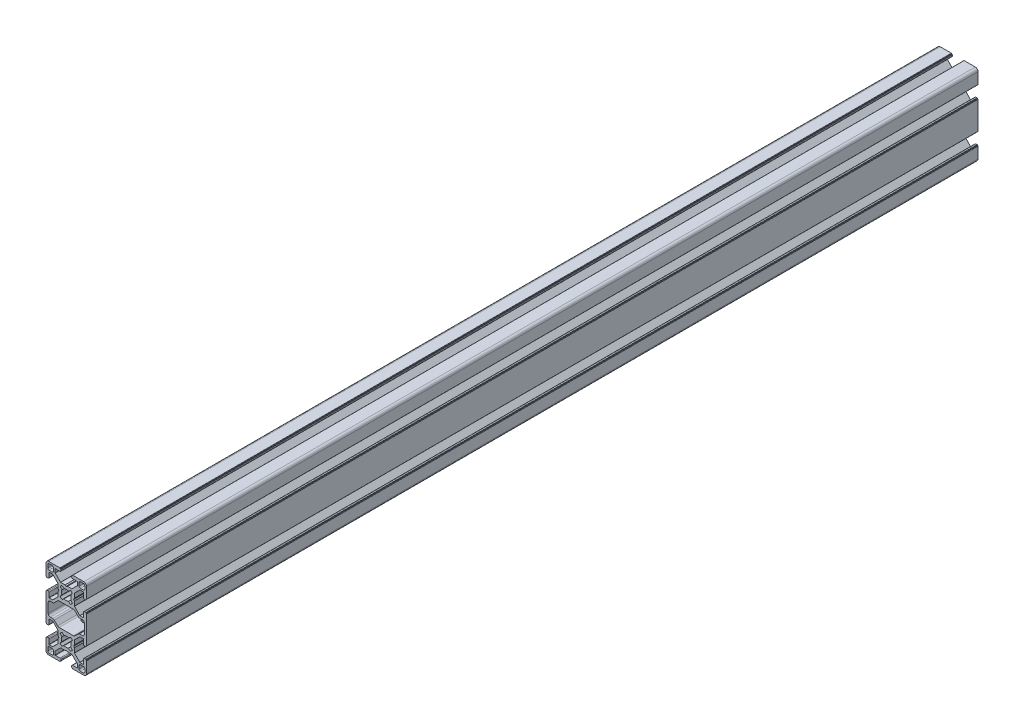
SolidWorks part; units mm, degrees
material "1060 Alloy"
ref_plane "Front" through (0, 0, 0) normal (0, 0, 1) x (1, 0, 0)
ref_plane "Top" through (0, 0, 0) normal (0, 1, 0) x (1, 0, 0)
ref_plane "Right" through (0, 0, 0) normal (1, 0, 0) x (0, 0, -1)
ref_plane "Plane1" through (0, 0, 25) normal (0, 0, 1) x (1, 0, 0)
sketch "Sketch1" plane through (0, 0, 25) normal (0, 0, 1) x (1, 0, 0)
  line L0 (-9.5, 12.7) -> (-9.5, 10.5)
  line L1 (-10.5, 9.5) -> (-12.7, 9.5)
  line L2 (-13.7, 10.5) -> (-13.7, 12.7)
  line L3 (-12.7, 13.7) -> (-10.5, 13.7)
  line L4 (12.7, 9.5) -> (10.5, 9.5)
  line L5 (9.5, 10.5) -> (9.5, 12.7)
  line L6 (10.5, 13.7) -> (12.7, 13.7)
  line L7 (13.7, 12.7) -> (13.7, 10.5)
  line L8 (-12.7, -39.5) -> (-10.5, -39.5)
  line L9 (-9.5, -40.5) -> (-9.5, -42.7)
  line L10 (-10.5, -43.7) -> (-12.7, -43.7)
  line L11 (-13.7, -42.7) -> (-13.7, -40.5)
  line L12 (9.5, -42.7) -> (9.5, -40.5)
  line L13 (10.5, -39.5) -> (12.7, -39.5)
  line L14 (13.7, -40.5) -> (13.7, -42.7)
  line L15 (12.7, -43.7) -> (10.5, -43.7)
  line L16 (-3.2806, 1.6001) -> (-4.5184, 3.1359)
  line L17 (-3.1547, 4.5053) -> (-1.6001, 3.2806)
  line L18 (1.6001, 3.2806) -> (3.1547, 4.5053)
  line L19 (4.5184, 3.1359) -> (3.2806, 1.6001)
  line L20 (3.2806, -1.6001) -> (4.5184, -3.1359)
  line L21 (3.1547, -4.5053) -> (1.6001, -3.2806)
  line L22 (-1.6001, -3.2806) -> (-3.1547, -4.5053)
  line L23 (-4.5184, -3.1359) -> (-3.2806, -1.6001)
  line L24 (-4.5184, -33.1359) -> (-3.2806, -31.6001)
  line L25 (-3.2806, -28.3999) -> (-4.5184, -26.8641)
  line L26 (-3.1547, -25.4947) -> (-1.6001, -26.7194)
  line L27 (1.6001, -26.7194) -> (3.1547, -25.4947)
  line L28 (4.5184, -26.8641) -> (3.2806, -28.3999)
  line L29 (3.2806, -31.6001) -> (4.5184, -33.1359)
  line L30 (3.1547, -34.5053) -> (1.6001, -33.2806)
  line L31 (-1.6001, -33.2806) -> (-3.1547, -34.5053)
  line L32 (8.9272, -20.5393) -> (6.4104, -23.0562)
  line L33 (5.3497, -23.4955) -> (-5.3497, -23.4955)
  line L34 (-6.4104, -23.0562) -> (-8.9272, -20.5393)
  line L35 (-9.9879, -20.1) -> (-11.85, -20.1)
  line L36 (-13.35, -18.6) -> (-13.35, -11.4)
  line L37 (-11.85, -9.9) -> (-9.9879, -9.9)
  line L38 (-8.9272, -9.4607) -> (-6.4104, -6.9438)
  line L39 (-5.3497, -6.5045) -> (5.3497, -6.5045)
  line L40 (6.4104, -6.9438) -> (8.9272, -9.4607)
  line L41 (9.9879, -9.9) -> (11.85, -9.9)
  line L42 (13.35, -11.4) -> (13.35, -18.6)
  line L43 (11.85, -20.1) -> (9.9879, -20.1)
  line L44 (13.4, -25.95) -> (14.3, -25.95)
  line L45 (14.5, -25.75) -> (14.5, -25.65)
  line L46 (14.7, -25.45) -> (14.8, -25.45)
  line L47 (15, -25.25) -> (15, -4.75)
  line L48 (14.8, -4.55) -> (14.7, -4.55)
  line L49 (14.5, -4.35) -> (14.5, -4.25)
  line L50 (14.3, -4.05) -> (13.4, -4.05)
  line L51 (12.8, -4.65) -> (12.8, -8.05)
  line L52 (12.6, -8.25) -> (10.1328, -8.25)
  line L53 (9.9914, -8.1914) -> (6.063, -4.263)
  line L54 (6.0045, -4.1216) -> (6.0045, -0.9)
  line L55 (6.0045, -0.9) -> (5.5426, -0.1)
  line L56 (5.5426, 0.1) -> (6.0045, 0.9)
  line L57 (6.0045, 0.9) -> (6.0045, 4.1216)
  line L58 (6.063, 4.263) -> (9.9914, 8.1914)
  line L59 (10.1328, 8.25) -> (12.6, 8.25)
  line L60 (12.8, 8.05) -> (12.8, 4.65)
  line L61 (13.4, 4.05) -> (14.3, 4.05)
  line L62 (14.5, 4.25) -> (14.5, 4.35)
  line L63 (14.7, 4.55) -> (14.8, 4.55)
  line L64 (15, 4.75) -> (15, 13)
  line L65 (13, 15) -> (4.75, 15)
  line L66 (4.55, 14.8) -> (4.55, 14.7)
  line L67 (4.35, 14.5) -> (4.25, 14.5)
  line L68 (4.05, 14.3) -> (4.05, 13.4)
  line L69 (4.65, 12.8) -> (8.05, 12.8)
  line L70 (8.25, 12.6) -> (8.25, 10.1328)
  line L71 (8.1914, 9.9914) -> (4.2586, 6.0586)
  line L72 (4.1172, 6) -> (0.9, 6)
  line L73 (0.9, 6) -> (0.1019, 5.5392)
  line L74 (-0.1019, 5.5392) -> (-0.9, 6)
  line L75 (-0.9, 6) -> (-4.1172, 6)
  line L76 (-4.2586, 6.0586) -> (-8.1914, 9.9914)
  line L77 (-8.25, 10.1328) -> (-8.25, 12.6)
  line L78 (-8.05, 12.8) -> (-4.65, 12.8)
  line L79 (-4.05, 13.4) -> (-4.05, 14.3)
  line L80 (-4.25, 14.5) -> (-4.35, 14.5)
  line L81 (-4.55, 14.7) -> (-4.55, 14.8)
  line L82 (-4.75, 15) -> (-13, 15)
  line L83 (-15, 13) -> (-15, 4.75)
  line L84 (-14.8, 4.55) -> (-14.7, 4.55)
  line L85 (-14.5, 4.35) -> (-14.5, 4.25)
  line L86 (-14.3, 4.05) -> (-13.4, 4.05)
  line L87 (-12.8, 4.65) -> (-12.8, 8.05)
  line L88 (-12.6, 8.25) -> (-10.1328, 8.25)
  line L89 (-9.9914, 8.1914) -> (-6.063, 4.263)
  line L90 (-6.0045, 4.1216) -> (-6.0045, 0.9)
  line L91 (-6.0045, 0.9) -> (-5.5426, 0.1)
  line L92 (-5.5426, -0.1) -> (-6.0045, -0.9)
  line L93 (-6.0045, -0.9) -> (-6.0045, -4.1216)
  line L94 (-6.063, -4.263) -> (-9.9914, -8.1914)
  line L95 (-10.1328, -8.25) -> (-12.6, -8.25)
  line L96 (-12.8, -8.05) -> (-12.8, -4.65)
  line L97 (-13.4, -4.05) -> (-14.3, -4.05)
  line L98 (-14.5, -4.25) -> (-14.5, -4.35)
  line L99 (-14.7, -4.55) -> (-14.8, -4.55)
  line L100 (-15, -4.75) -> (-15, -25.25)
  line L101 (-14.8, -25.45) -> (-14.7, -25.45)
  line L102 (-14.5, -25.65) -> (-14.5, -25.75)
  line L103 (-14.3, -25.95) -> (-13.4, -25.95)
  line L104 (-12.8, -25.35) -> (-12.8, -21.95)
  line L105 (-12.6, -21.75) -> (-10.1328, -21.75)
  line L106 (-9.9914, -21.8086) -> (-6.063, -25.737)
  line L107 (-6.0045, -25.8784) -> (-6.0045, -29.1)
  line L108 (-6.0045, -29.1) -> (-5.5426, -29.9)
  line L109 (-5.5426, -30.1) -> (-6.0045, -30.9)
  line L110 (-6.0045, -30.9) -> (-6.0045, -34.1216)
  line L111 (-6.063, -34.263) -> (-9.9914, -38.1914)
  line L112 (-10.1328, -38.25) -> (-12.6, -38.25)
  line L113 (-12.8, -38.05) -> (-12.8, -34.65)
  line L114 (-13.4, -34.05) -> (-14.3, -34.05)
  line L115 (-14.5, -34.25) -> (-14.5, -34.35)
  line L116 (-14.7, -34.55) -> (-14.8, -34.55)
  line L117 (-15, -34.75) -> (-15, -43)
  line L118 (-13, -45) -> (-4.75, -45)
  line L119 (-4.55, -44.8) -> (-4.55, -44.7)
  line L120 (-4.35, -44.5) -> (-4.25, -44.5)
  line L121 (-4.05, -44.3) -> (-4.05, -43.4)
  line L122 (-4.65, -42.8) -> (-8.05, -42.8)
  line L123 (-8.25, -42.6) -> (-8.25, -40.1328)
  line L124 (-8.1914, -39.9914) -> (-4.2586, -36.0586)
  line L125 (-4.1172, -36) -> (-0.9, -36)
  line L126 (-0.9, -36) -> (-0.1019, -35.5392)
  line L127 (0.1019, -35.5392) -> (0.9, -36)
  line L128 (0.9, -36) -> (4.1172, -36)
  line L129 (4.2586, -36.0586) -> (8.1914, -39.9914)
  line L130 (8.25, -40.1328) -> (8.25, -42.6)
  line L131 (8.05, -42.8) -> (4.65, -42.8)
  line L132 (4.05, -43.4) -> (4.05, -44.3)
  line L133 (4.25, -44.5) -> (4.35, -44.5)
  line L134 (4.55, -44.7) -> (4.55, -44.8)
  line L135 (4.75, -45) -> (13, -45)
  line L136 (15, -43) -> (15, -34.75)
  line L137 (14.8, -34.55) -> (14.7, -34.55)
  line L138 (14.5, -34.35) -> (14.5, -34.25)
  line L139 (14.3, -34.05) -> (13.4, -34.05)
  line L140 (12.8, -34.65) -> (12.8, -38.05)
  line L141 (12.6, -38.25) -> (10.1328, -38.25)
  line L142 (9.9914, -38.1914) -> (6.063, -34.263)
  line L143 (6.0045, -34.1216) -> (6.0045, -30.9)
  line L144 (6.0045, -30.9) -> (5.5426, -30.1)
  line L145 (5.5426, -29.9) -> (6.0045, -29.1)
  line L146 (6.0045, -29.1) -> (6.0045, -25.8784)
  line L147 (6.063, -25.737) -> (9.9914, -21.8086)
  line L148 (10.1328, -21.75) -> (12.6, -21.75)
  line L149 (12.8, -21.95) -> (12.8, -25.35)
  arc A0 (-9.5, 10.5) -> (-10.5, 9.5) centre (-10.5, 10.5) cw
  arc A1 (-12.7, 9.5) -> (-13.7, 10.5) centre (-12.7, 10.5) cw
  arc A2 (-13.7, 12.7) -> (-12.7, 13.7) centre (-12.7, 12.7) cw
  arc A3 (-10.5, 13.7) -> (-9.5, 12.7) centre (-10.5, 12.7) cw
  arc A4 (10.5, 9.5) -> (9.5, 10.5) centre (10.5, 10.5) cw
  arc A5 (9.5, 12.7) -> (10.5, 13.7) centre (10.5, 12.7) cw
  arc A6 (12.7, 13.7) -> (13.7, 12.7) centre (12.7, 12.7) cw
  arc A7 (13.7, 10.5) -> (12.7, 9.5) centre (12.7, 10.5) cw
  arc A8 (-10.5, -39.5) -> (-9.5, -40.5) centre (-10.5, -40.5) cw
  arc A9 (-9.5, -42.7) -> (-10.5, -43.7) centre (-10.5, -42.7) cw
  arc A10 (-12.7, -43.7) -> (-13.7, -42.7) centre (-12.7, -42.7) cw
  arc A11 (-13.7, -40.5) -> (-12.7, -39.5) centre (-12.7, -40.5) cw
  arc A12 (9.5, -40.5) -> (10.5, -39.5) centre (10.5, -40.5) cw
  arc A13 (12.7, -39.5) -> (13.7, -40.5) centre (12.7, -40.5) cw
  arc A14 (13.7, -42.7) -> (12.7, -43.7) centre (12.7, -42.7) cw
  arc A15 (10.5, -43.7) -> (9.5, -42.7) centre (10.5, -42.7) cw
  arc A16 (-4.5184, 3.1359) -> (-3.1547, 4.5053) centre (0, 0) cw
  arc A17 (-1.6001, 3.2806) -> (1.6001, 3.2806) centre (0, 0) cw
  arc A18 (3.1547, 4.5053) -> (4.5184, 3.1359) centre (0, 0) cw
  arc A19 (3.2806, 1.6001) -> (3.2806, -1.6001) centre (0, 0) cw
  arc A20 (4.5184, -3.1359) -> (3.1547, -4.5053) centre (0, 0) cw
  arc A21 (1.6001, -3.2806) -> (-1.6001, -3.2806) centre (0, 0) cw
  arc A22 (-3.1547, -4.5053) -> (-4.5184, -3.1359) centre (0, 0) cw
  arc A23 (-3.2806, -1.6001) -> (-3.2806, 1.6001) centre (0, 0) cw
  arc A24 (-3.2806, -31.6001) -> (-3.2806, -28.3999) centre (0, -30) cw
  arc A25 (-4.5184, -26.8641) -> (-3.1547, -25.4947) centre (0, -30) cw
  arc A26 (-1.6001, -26.7194) -> (1.6001, -26.7194) centre (0, -30) cw
  arc A27 (3.1547, -25.4947) -> (4.5184, -26.8641) centre (0, -30) cw
  arc A28 (3.2806, -28.3999) -> (3.2806, -31.6001) centre (0, -30) cw
  arc A29 (4.5184, -33.1359) -> (3.1547, -34.5053) centre (0, -30) cw
  arc A30 (1.6001, -33.2806) -> (-1.6001, -33.2806) centre (0, -30) cw
  arc A31 (-3.1547, -34.5053) -> (-4.5184, -33.1359) centre (0, -30) cw
  arc A32 (6.4104, -23.0562) -> (5.3497, -23.4955) centre (5.3497, -21.9955) cw
  arc A33 (-5.3497, -23.4955) -> (-6.4104, -23.0562) centre (-5.3497, -21.9955) cw
  arc A34 (-8.9272, -20.5393) -> (-9.9879, -20.1) centre (-9.9879, -21.6) ccw
  arc A35 (-11.85, -20.1) -> (-13.35, -18.6) centre (-11.85, -18.6) cw
  arc A36 (-13.35, -11.4) -> (-11.85, -9.9) centre (-11.85, -11.4) cw
  arc A37 (-9.9879, -9.9) -> (-8.9272, -9.4607) centre (-9.9879, -8.4) ccw
  arc A38 (-6.4104, -6.9438) -> (-5.3497, -6.5045) centre (-5.3497, -8.0045) cw
  arc A39 (5.3497, -6.5045) -> (6.4104, -6.9438) centre (5.3497, -8.0045) cw
  arc A40 (8.9272, -9.4607) -> (9.9879, -9.9) centre (9.9879, -8.4) ccw
  arc A41 (11.85, -9.9) -> (13.35, -11.4) centre (11.85, -11.4) cw
  arc A42 (13.35, -18.6) -> (11.85, -20.1) centre (11.85, -18.6) cw
  arc A43 (9.9879, -20.1) -> (8.9272, -20.5393) centre (9.9879, -21.6) ccw
  arc A44 (12.8, -25.35) -> (13.4, -25.95) centre (13.4, -25.35) ccw
  arc A45 (14.3, -25.95) -> (14.5, -25.75) centre (14.3, -25.75) ccw
  arc A46 (14.5, -25.65) -> (14.7, -25.45) centre (14.7, -25.65) cw
  arc A47 (14.8, -25.45) -> (15, -25.25) centre (14.8, -25.25) ccw
  arc A48 (15, -4.75) -> (14.8, -4.55) centre (14.8, -4.75) ccw
  arc A49 (14.7, -4.55) -> (14.5, -4.35) centre (14.7, -4.35) cw
  arc A50 (14.5, -4.25) -> (14.3, -4.05) centre (14.3, -4.25) ccw
  arc A51 (13.4, -4.05) -> (12.8, -4.65) centre (13.4, -4.65) ccw
  arc A52 (12.8, -8.05) -> (12.6, -8.25) centre (12.6, -8.05) cw
  arc A53 (10.1328, -8.25) -> (9.9914, -8.1914) centre (10.1328, -8.05) cw
  arc A54 (6.063, -4.263) -> (6.0045, -4.1216) centre (6.2045, -4.1216) cw
  arc A55 (5.5426, -0.1) -> (5.5426, 0.1) centre (5.7158, 0) cw
  arc A56 (6.0045, 4.1216) -> (6.063, 4.263) centre (6.2045, 4.1216) cw
  arc A57 (9.9914, 8.1914) -> (10.1328, 8.25) centre (10.1328, 8.05) cw
  arc A58 (12.6, 8.25) -> (12.8, 8.05) centre (12.6, 8.05) cw
  arc A59 (12.8, 4.65) -> (13.4, 4.05) centre (13.4, 4.65) ccw
  arc A60 (14.3, 4.05) -> (14.5, 4.25) centre (14.3, 4.25) ccw
  arc A61 (14.5, 4.35) -> (14.7, 4.55) centre (14.7, 4.35) cw
  arc A62 (14.8, 4.55) -> (15, 4.75) centre (14.8, 4.75) ccw
  arc A63 (15, 13) -> (13, 15) centre (13, 13) ccw
  arc A64 (4.75, 15) -> (4.55, 14.8) centre (4.75, 14.8) ccw
  arc A65 (4.55, 14.7) -> (4.35, 14.5) centre (4.35, 14.7) cw
  arc A66 (4.25, 14.5) -> (4.05, 14.3) centre (4.25, 14.3) ccw
  arc A67 (4.05, 13.4) -> (4.65, 12.8) centre (4.65, 13.4) ccw
  arc A68 (8.05, 12.8) -> (8.25, 12.6) centre (8.05, 12.6) cw
  arc A69 (8.25, 10.1328) -> (8.1914, 9.9914) centre (8.05, 10.1328) cw
  arc A70 (4.2586, 6.0586) -> (4.1172, 6) centre (4.1172, 6.2) cw
  arc A71 (0.1019, 5.5392) -> (-0.1019, 5.5392) centre (0, 5.7158) cw
  arc A72 (-4.1172, 6) -> (-4.2586, 6.0586) centre (-4.1172, 6.2) cw
  arc A73 (-8.1914, 9.9914) -> (-8.25, 10.1328) centre (-8.05, 10.1328) cw
  arc A74 (-8.25, 12.6) -> (-8.05, 12.8) centre (-8.05, 12.6) cw
  arc A75 (-4.65, 12.8) -> (-4.05, 13.4) centre (-4.65, 13.4) ccw
  arc A76 (-4.05, 14.3) -> (-4.25, 14.5) centre (-4.25, 14.3) ccw
  arc A77 (-4.35, 14.5) -> (-4.55, 14.7) centre (-4.35, 14.7) cw
  arc A78 (-4.55, 14.8) -> (-4.75, 15) centre (-4.75, 14.8) ccw
  arc A79 (-13, 15) -> (-15, 13) centre (-13, 13) ccw
  arc A80 (-15, 4.75) -> (-14.8, 4.55) centre (-14.8, 4.75) ccw
  arc A81 (-14.7, 4.55) -> (-14.5, 4.35) centre (-14.7, 4.35) cw
  arc A82 (-14.5, 4.25) -> (-14.3, 4.05) centre (-14.3, 4.25) ccw
  arc A83 (-13.4, 4.05) -> (-12.8, 4.65) centre (-13.4, 4.65) ccw
  arc A84 (-12.8, 8.05) -> (-12.6, 8.25) centre (-12.6, 8.05) cw
  arc A85 (-10.1328, 8.25) -> (-9.9914, 8.1914) centre (-10.1328, 8.05) cw
  arc A86 (-6.063, 4.263) -> (-6.0045, 4.1216) centre (-6.2045, 4.1216) cw
  arc A87 (-5.5426, 0.1) -> (-5.5426, -0.1) centre (-5.7158, 0) cw
  arc A88 (-6.0045, -4.1216) -> (-6.063, -4.263) centre (-6.2045, -4.1216) cw
  arc A89 (-9.9914, -8.1914) -> (-10.1328, -8.25) centre (-10.1328, -8.05) cw
  arc A90 (-12.6, -8.25) -> (-12.8, -8.05) centre (-12.6, -8.05) cw
  arc A91 (-12.8, -4.65) -> (-13.4, -4.05) centre (-13.4, -4.65) ccw
  arc A92 (-14.3, -4.05) -> (-14.5, -4.25) centre (-14.3, -4.25) ccw
  arc A93 (-14.5, -4.35) -> (-14.7, -4.55) centre (-14.7, -4.35) cw
  arc A94 (-14.8, -4.55) -> (-15, -4.75) centre (-14.8, -4.75) ccw
  arc A95 (-15, -25.25) -> (-14.8, -25.45) centre (-14.8, -25.25) ccw
  arc A96 (-14.7, -25.45) -> (-14.5, -25.65) centre (-14.7, -25.65) cw
  arc A97 (-14.5, -25.75) -> (-14.3, -25.95) centre (-14.3, -25.75) ccw
  arc A98 (-13.4, -25.95) -> (-12.8, -25.35) centre (-13.4, -25.35) ccw
  arc A99 (-12.8, -21.95) -> (-12.6, -21.75) centre (-12.6, -21.95) cw
  arc A100 (-10.1328, -21.75) -> (-9.9914, -21.8086) centre (-10.1328, -21.95) cw
  arc A101 (-6.063, -25.737) -> (-6.0045, -25.8784) centre (-6.2045, -25.8784) cw
  arc A102 (-5.5426, -29.9) -> (-5.5426, -30.1) centre (-5.7158, -30) cw
  arc A103 (-6.0045, -34.1216) -> (-6.063, -34.263) centre (-6.2045, -34.1216) cw
  arc A104 (-9.9914, -38.1914) -> (-10.1328, -38.25) centre (-10.1328, -38.05) cw
  arc A105 (-12.6, -38.25) -> (-12.8, -38.05) centre (-12.6, -38.05) cw
  arc A106 (-12.8, -34.65) -> (-13.4, -34.05) centre (-13.4, -34.65) ccw
  arc A107 (-14.3, -34.05) -> (-14.5, -34.25) centre (-14.3, -34.25) ccw
  arc A108 (-14.5, -34.35) -> (-14.7, -34.55) centre (-14.7, -34.35) cw
  arc A109 (-14.8, -34.55) -> (-15, -34.75) centre (-14.8, -34.75) ccw
  arc A110 (-15, -43) -> (-13, -45) centre (-13, -43) ccw
  arc A111 (-4.75, -45) -> (-4.55, -44.8) centre (-4.75, -44.8) ccw
  arc A112 (-4.55, -44.7) -> (-4.35, -44.5) centre (-4.35, -44.7) cw
  arc A113 (-4.25, -44.5) -> (-4.05, -44.3) centre (-4.25, -44.3) ccw
  arc A114 (-4.05, -43.4) -> (-4.65, -42.8) centre (-4.65, -43.4) ccw
  arc A115 (-8.05, -42.8) -> (-8.25, -42.6) centre (-8.05, -42.6) cw
  arc A116 (-8.25, -40.1328) -> (-8.1914, -39.9914) centre (-8.05, -40.1328) cw
  arc A117 (-4.2586, -36.0586) -> (-4.1172, -36) centre (-4.1172, -36.2) cw
  arc A118 (-0.1019, -35.5392) -> (0.1019, -35.5392) centre (0, -35.7158) cw
  arc A119 (4.1172, -36) -> (4.2586, -36.0586) centre (4.1172, -36.2) cw
  arc A120 (8.1914, -39.9914) -> (8.25, -40.1328) centre (8.05, -40.1328) cw
  arc A121 (8.25, -42.6) -> (8.05, -42.8) centre (8.05, -42.6) cw
  arc A122 (4.65, -42.8) -> (4.05, -43.4) centre (4.65, -43.4) ccw
  arc A123 (4.05, -44.3) -> (4.25, -44.5) centre (4.25, -44.3) ccw
  arc A124 (4.35, -44.5) -> (4.55, -44.7) centre (4.35, -44.7) cw
  arc A125 (4.55, -44.8) -> (4.75, -45) centre (4.75, -44.8) ccw
  arc A126 (13, -45) -> (15, -43) centre (13, -43) ccw
  arc A127 (15, -34.75) -> (14.8, -34.55) centre (14.8, -34.75) ccw
  arc A128 (14.7, -34.55) -> (14.5, -34.35) centre (14.7, -34.35) cw
  arc A129 (14.5, -34.25) -> (14.3, -34.05) centre (14.3, -34.25) ccw
  arc A130 (13.4, -34.05) -> (12.8, -34.65) centre (13.4, -34.65) ccw
  arc A131 (12.8, -38.05) -> (12.6, -38.25) centre (12.6, -38.05) cw
  arc A132 (10.1328, -38.25) -> (9.9914, -38.1914) centre (10.1328, -38.05) cw
  arc A133 (6.063, -34.263) -> (6.0045, -34.1216) centre (6.2045, -34.1216) cw
  arc A134 (5.5426, -30.1) -> (5.5426, -29.9) centre (5.7158, -30) cw
  arc A135 (6.0045, -25.8784) -> (6.063, -25.737) centre (6.2045, -25.8784) cw
  arc A136 (9.9914, -21.8086) -> (10.1328, -21.75) centre (10.1328, -21.95) cw
  arc A137 (12.6, -21.75) -> (12.8, -21.95) centre (12.6, -21.95) cw
extrude "Boss-Extrude1" add sketch "Sketch1" against normal blind 660
sketch "Sketch2" plane through (0, 15, 0) normal (0, 1, 0) x (1, 0, 0)
  line L0 (-15, 620) -> (15, 620) construction
  line L1 (-15, 635) -> (-15, -25) construction
  line L2 (15, 635) -> (15, -25) construction
  line L3 (-4.75, 635) -> (-13, 635) construction
  line L4 (-15, -10) -> (15, -10) construction
  line L5 (-4.75, -25) -> (-13, -25) construction
  circle A0 centre (0, 620) radius 3
  circle A1 centre (0, -10) radius 3
  dimension "D2" = 6
  dimension "D4" = 6
  dimension "D1" = 15
  dimension "D3" = 15
extrude "Cut-Extrude1" cut sketch "Sketch2" against normal through all
sketch "Sketch3" plane through (15, 0, 0) normal (1, 0, 0) x (0, 0, -1)
  line L0 (-25, 0) -> (635, 0) construction
  line L1 (-25, 0.1) -> (-25, -0.1) construction
  line L2 (635, -0.1) -> (635, 0.1) construction
  line L3 (305, 15) -> (305, -45) construction
  line L4 (635, 15) -> (-25, 15) construction
  line L5 (635, -45) -> (-25, -45) construction
  circle A0 centre (305, 0) radius 3
  dimension "D1" = 6
extrude "Cut-Extrude2" cut sketch "Sketch3" against normal through all
